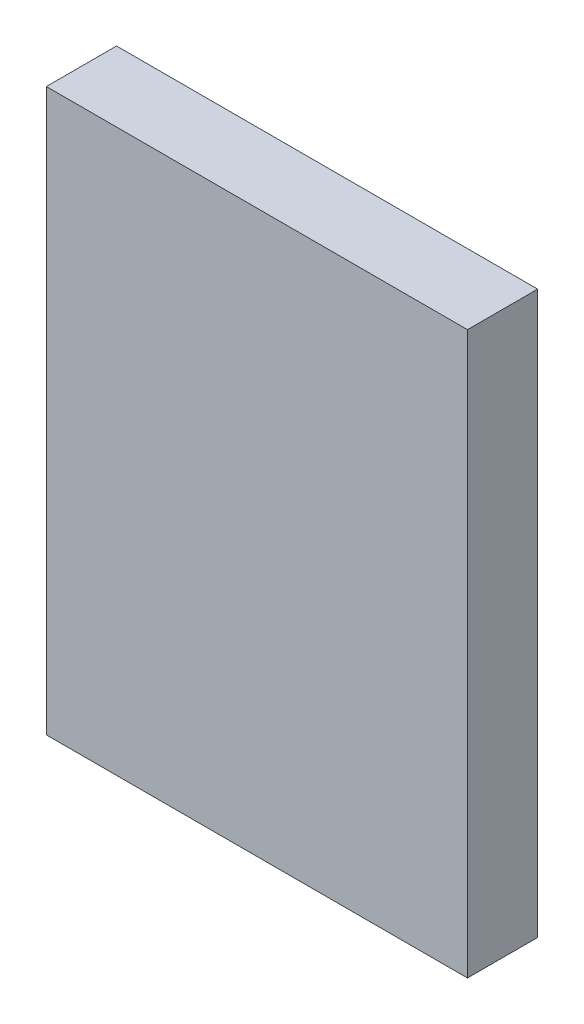
SolidWorks part; units mm, degrees
ref_plane "Front Plane" through (0, 0, 0) normal (0, 0, 1) x (1, 0, 0)
ref_plane "Top Plane" through (0, 0, 0) normal (0, 1, 0) x (1, 0, 0)
ref_plane "Right Plane" through (0, 0, 0) normal (1, 0, 0) x (0, 0, -1)
sketch "Sketch1" plane through (0, 0, 0) normal (0, 0, 1) x (1, 0, 0)
  line L1 (-15, 20) -> (15, 20)
  line L2 (-15, 20) -> (-15, -20)
  line L3 (-15, -20) -> (15, -20)
  line L4 (15, 20) -> (15, -20)
  line L5 (-15, 20) -> (15, -20) construction
  line L6 (-15, -20) -> (15, 20) construction
  point P0 (0, 0)
  dimension "D1" = 30
  dimension "D2" = 40
extrude "Boss-Extrude1" add sketch "Sketch1" along normal blind 5
